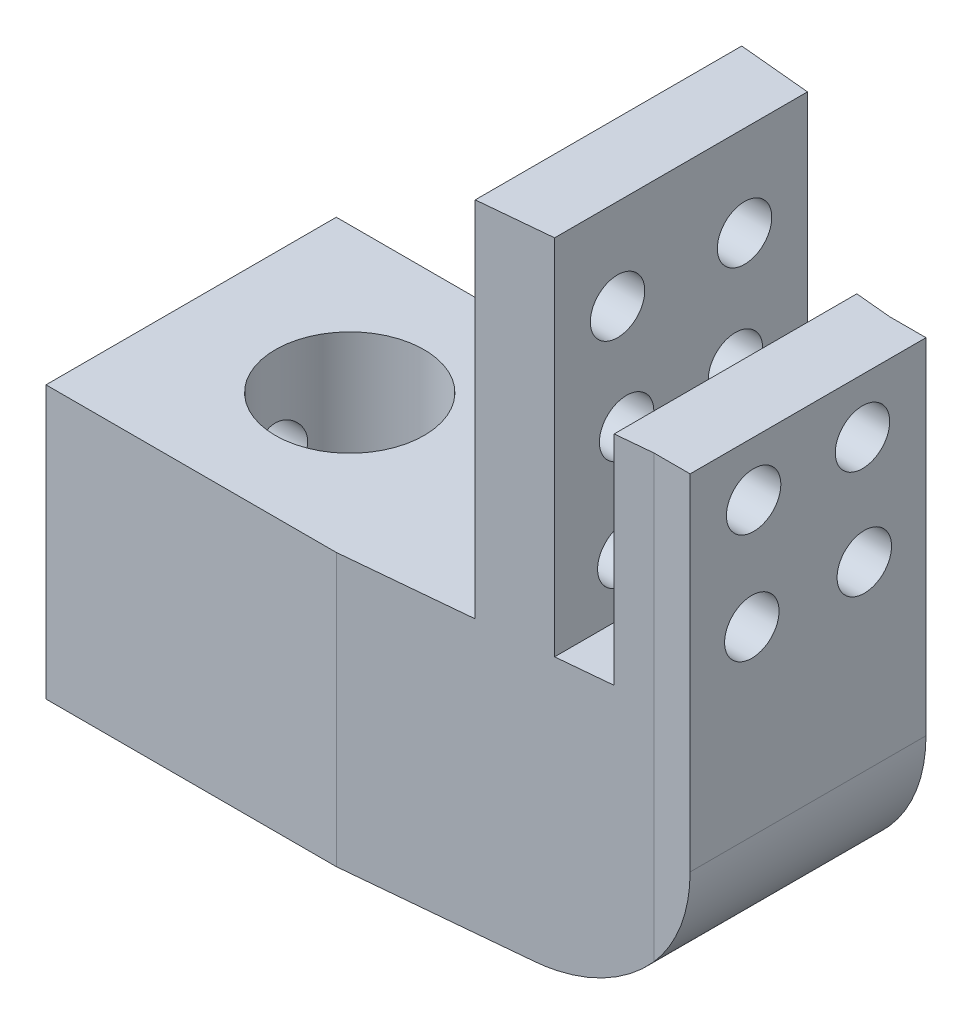
SolidWorks part; units mm, degrees
ref_plane "Front Plane" through (0, 0, 0) normal (0, 0, 1) x (1, 0, 0)
ref_plane "Top Plane" through (0, 0, 0) normal (0, 1, 0) x (1, 0, 0)
ref_plane "Right Plane" through (0, 0, 0) normal (1, 0, 0) x (0, 0, -1)
sketch "Sketch2" plane through (0, 0, 0) normal (0, 1, 0) x (1, 0, 0)
  line L0 (-16, -8) -> (-16, 8)
  line L1 (-18.15, 0) -> (18.15, 0) construction
  line L2 (-16, 8) -> (0, 8)
  line L3 (0, -8.8) -> (0, 8.8) construction
  line L4 (0, 8) -> (16, 6.5)
  line L5 (16, 6.5) -> (21, 6.5)
  line L6 (21, 6.5) -> (21, -6.5)
  line L8 (16, -6.5) -> (21, -6.5)
  line L9 (0, -8) -> (16, -6.5)
  line L10 (-16, -8) -> (0, -8)
  point P11 (21, 0)
  point P14 (-16, 0)
  dimension "D1" = 6.5
  dimension "D2" = 8
  dimension "D3" = 16
  dimension "D4" = 16
  dimension "D5" = 5
extrude "Boss-Extrude1" add sketch "Sketch2" along normal mid plane 15
sketch "Sketch4" plane through (0, 7.5, 0) normal (0, 1, 0) x (1, 0, 0)
  line L0 (-18.15, 0) -> (18.15, 0) construction
  circle A0 centre (-7.26, 0) radius 4.1
  dimension "D1" = 8.2
extrude "Cut-Extrude1" cut sketch "Sketch4" against normal blind 10
sketch "Sketch5" plane through (0, -2.5, 0) normal (0, 1, 0) x (1, 0, 0)
  circle A0 centre (-7.26, 0) radius 1.5
  dimension "D1" = 3
extrude "Cut-Extrude2" cut sketch "Sketch5" against normal up to surface (5 mm away) up to face at (5.25, -7.5, 0)
sketch "Sketch7" plane through (-16, 0, 0) normal (-1, 0, 0) x (0, 0, 1)
  line L0 (0, -18.15) -> (0, 18.15) construction
  line L2 (-8, 7.5) -> (8, 7.5) construction
  circle A0 centre (0, 2.5) radius 1.5
  dimension "D1" = 3
  dimension "D2" = 5
extrude "Cut-Extrude4" cut sketch "Sketch7" against normal up to surface (4.9243 mm away)
sketch "Sketch8" plane through (0, 7.5, 0) normal (0, 1, 0) x (1, 0, 0)
  line L0 (7, 7.3437) -> (7, -7.3437)
  line L8 (0, 8) -> (-16, 8)
  line L9 (-16, 8) -> (-16, -8)
  line L10 (-16, -8) -> (0, -8)
  line L11 (0, -8) -> (16, -6.5)
  line L12 (16, -6.5) -> (21, -6.5)
  line L13 (21, -6.5) -> (21, 6.5)
  line L14 (21, 6.5) -> (16, 6.5)
  line L15 (16, 6.5) -> (0, 8)
  line L19 (7, -7.3437) -> (16, -6.5)
  line L20 (16, -6.5) -> (21, -6.5)
  line L21 (21, -6.5) -> (21, 6.5)
  line L22 (21, 6.5) -> (16, 6.5)
  line L23 (16, 6.5) -> (7, 7.3437)
  dimension "D2" = 14
  dimension "D1" = 0
extrude "Boss-Extrude2" add sketch "Sketch8" along normal blind 20
sketch "Sketch11" plane through (0, 27.5, 0) normal (0, 1, 0) x (1, 0, 0)
  line L0 (11, 6.9687) -> (11, -6.9687)
  line L1 (16, 6.5) -> (7, 7.3437) construction
  line L2 (7, -7.3437) -> (16, -6.5) construction
  line L3 (11, -6.9687) -> (14, -6.6875)
  line L5 (11, 6.9687) -> (14, 6.6875)
  line L6 (14, -6.6875) -> (14, 6.6875)
  line L11 (7, 7.3437) -> (7, -7.3437) construction
  dimension "D1" = 3
  dimension "D2" = 4
extrude "Cut-Extrude5" cut sketch "Sketch11" against normal blind 20
sketch "Sketch12" plane through (0, 27.5, 0) normal (0, 1, 0) x (1, 0, 0)
  line L4 (14, 6.6875) -> (14, -6.6875)
  line L5 (16, -6.5) -> (21, -6.5)
  line L6 (21, -6.5) -> (21, 6.5)
  line L7 (21, 6.5) -> (16, 6.5)
  line L8 (14, 6.6875) -> (14, -6.6875)
  line L9 (16, -6.5) -> (21, -6.5)
  line L10 (21, -6.5) -> (21, 6.5)
  line L11 (21, 6.5) -> (16, 6.5)
  line L14 (14, -6.6875) -> (16, -6.5)
  line L15 (14, -6.6875) -> (16, -6.5)
  line L16 (16, 6.5) -> (14, 6.6875)
  line L17 (16, 6.5) -> (14, 6.6875)
  dimension "D1" = 0
extrude "Cut-Extrude6" cut sketch "Sketch12" against normal blind 8
sketch "Sketch13" plane through (21, 0, 0) normal (1, 0, 0) x (0, 0, -1)
  line L0 (0, 19.25) -> (0, -19.25) construction
  line L1 (-6.5, 19.5) -> (6.5, 19.5) construction
  circle A0 centre (-3, 16.5) radius 1.5
  circle A1 centre (3, 16.5) radius 1.5
  circle A2 centre (-3.1, 10.5) radius 1.5
  circle A3 centre (3.1, 10.5) radius 1.5
  dimension "D1" = 3
  dimension "D2" = 3
  dimension "D3" = 3
  dimension "D4" = 3
  dimension "D5" = 6
  dimension "D6" = 3
  dimension "D7" = 3
  dimension "D8" = 6
  dimension "D9" = 6.2
  dimension "D10" = 3.1
extrude "Cut-Extrude7" cut sketch "Sketch13" against normal blind 16
sketch "Sketch14" plane through (7, 0, 0) normal (-1, 0, 0) x (0, 0, 1)
  line L0 (0, -19.25) -> (0, 19.25) construction
  line L1 (-7.3437, 27.5) -> (7.3437, 27.5) construction
  circle A0 centre (-3.5, 22.5) radius 1.5
  circle A1 centre (3.5, 22.5) radius 1.5
  dimension "D1" = 3
  dimension "D2" = 3
  dimension "D3" = 7
  dimension "D4" = 3.5
  dimension "D5" = 5
extrude "Cut-Extrude8" cut sketch "Sketch14" against normal up to surface (4 mm away) up to face at (11, 16.5, -1.5)
sketch "Sketch15" plane through (7, 0, 0) normal (-1, 0, 0) x (0, 0, 1)
  line L1 (4.6588, 13.2) -> (1.5412, 13.2)
  line L2 (1.5412, 13.2) -> (-0.0177, 10.5)
  line L3 (-0.0177, 10.5) -> (1.5412, 7.8)
  line L4 (1.5412, 7.8) -> (4.6588, 7.8)
  line L5 (4.6588, 7.8) -> (6.2177, 10.5)
  line L6 (6.2177, 10.5) -> (4.6588, 13.2)
  circle A0 centre (3.1, 10.5) radius 2.7 construction
  dimension "D1" = 5.4
extrude "Cut-Extrude9" cut sketch "Sketch15" against normal blind 1 and the other way blind 1.6
mirror "Mirror1" about plane through (0, 0, 0) normal (0, 0, 1) of "Cut-Extrude9"
sketch "Sketch16" plane through (0, 19.5, 0) normal (0, 1, 0) x (1, 0, 0)
  line L0 (18, 6.5) -> (18, -6.5)
  line L6 (21, -6.5) -> (21, 6.5)
  line L7 (21, 6.5) -> (16, 6.5)
  line L8 (16, 6.5) -> (14, 6.6875)
  line L9 (14, 6.6875) -> (14, -6.6875)
  line L10 (14, -6.6875) -> (16, -6.5)
  line L11 (16, -6.5) -> (21, -6.5)
  line L12 (21, -6.5) -> (21, 6.5)
  line L13 (21, 6.5) -> (18, 6.5)
  line L17 (18, -6.5) -> (21, -6.5)
  dimension "D2" = 3
  dimension "D1" = 0
extrude "Cut-Extrude10" cut sketch "Sketch16" against normal through all
fillet "Fillet1" radius 8 1 edges at (18, -7.5, 0)
